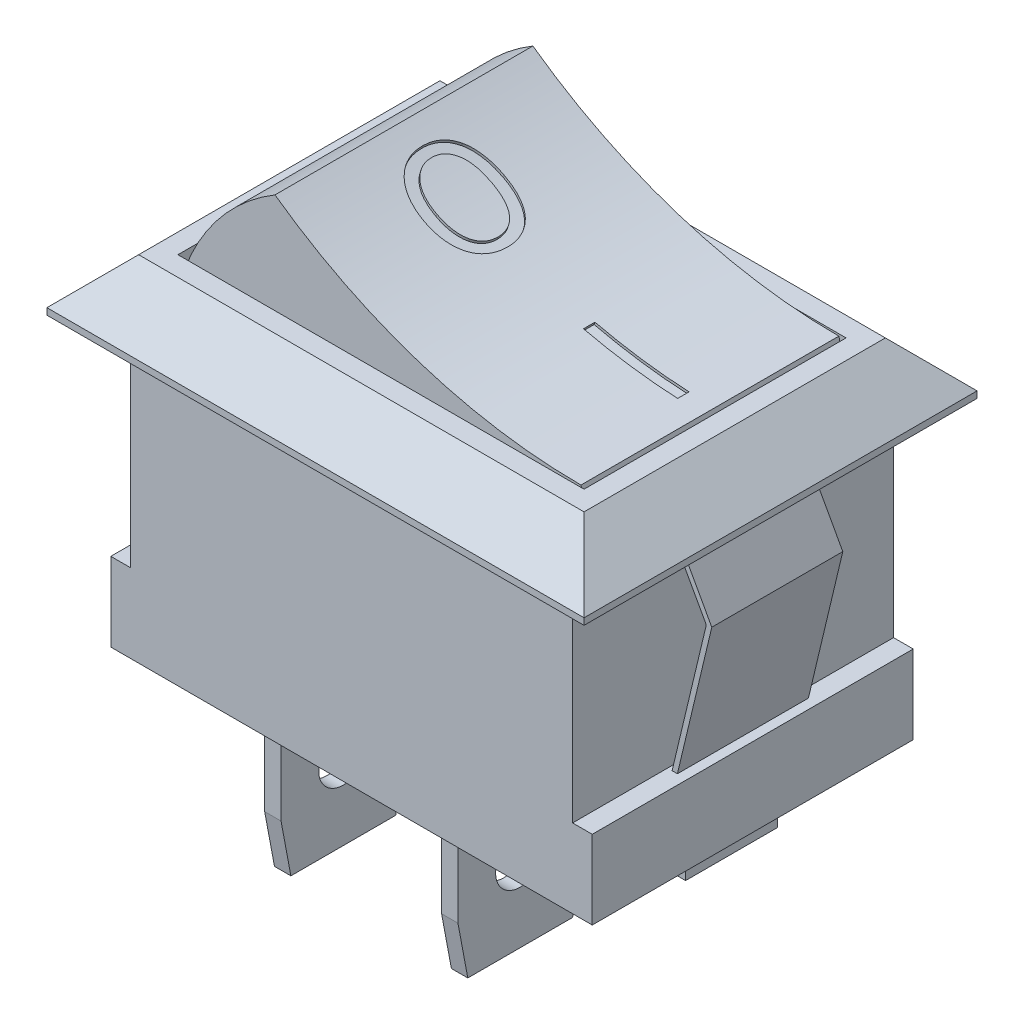
SolidWorks part; units mm, degrees
ref_plane "Front Plane" through (0, 0, 0) normal (0, 0, 1) x (1, 0, 0)
ref_plane "Top Plane" through (0, 0, 0) normal (0, 1, 0) x (1, 0, 0)
ref_plane "Right Plane" through (0, 0, 0) normal (1, 0, 0) x (0, 0, -1)
sketch "Sketch1" plane through (0, 0, 0) normal (0, 1, 0) x (1, 0, 0)
  line L1 (-9.3345, 6.223) -> (9.3345, 6.223)
  line L2 (-9.3345, 6.223) -> (-9.3345, -6.223)
  line L3 (-9.3345, -6.223) -> (9.3345, -6.223)
  line L4 (9.3345, 6.223) -> (9.3345, -6.223)
  line L5 (-9.3345, 6.223) -> (9.3345, -6.223) construction
  line L6 (-9.3345, -6.223) -> (9.3345, 6.223) construction
  point P0 (0, 0)
  dimension "D1" = 12.446
  dimension "D2" = 18.669
extrude "Boss-Extrude1" add sketch "Sketch1" along normal blind 11.303
sketch "Sketch2" plane through (9.3345, 0, 0) normal (1, 0, 0) x (0, 0, -1)
  line L0 (-6.223, 0) -> (6.223, 0) construction
  line L1 (-6.223, 11.303) -> (6.223, 11.303)
  line L2 (-6.223, 11.303) -> (-6.223, 3.048)
  line L3 (-6.223, 3.048) -> (6.223, 3.048)
  line L4 (6.223, 11.303) -> (6.223, 3.048)
  dimension "D1" = 3.048
extrude "Cut-Extrude1" cut sketch "Sketch2" against normal blind 0.762
sketch "Sketch3" plane through (0, 0, 0) normal (0, 0, 1) x (1, 0, 0)
  line L0 (8.2261, 0) -> (10.287, 8.636)
  line L1 (10.287, 8.636) -> (8.8725, 11.203)
  line L2 (0, 0) -> (0, 11.303) construction
  line L3 (-9.3345, 0) -> (9.3345, 0) construction
  line L4 (-9.3345, 11.303) -> (8.5725, 11.303) construction
  line L5 (0, 8.636) -> (10.287, 8.636) construction
  line L6 (8.5725, 3.048) -> (9.3345, 3.048) construction
  line L7 (8.5725, 11.303) -> (8.5725, 3.048) construction
  point P15 (8.9535, 3.048)
  dimension "D1" = 10.287
  dimension "D2" = 8.636
  dimension "D3" = 0.3
  dimension "D4" = 0.1
extrude "Extrude-Thin1" add sketch "Sketch3" along normal mid plane 5.08 thin thin type one direction reverse wall 0.2
mirror "Mirror1" about plane through (0, 0, 0) normal (1, 0, 0) of "Cut-Extrude1", "Extrude-Thin1"
sketch "Sketch4" plane through (0, 11.303, 0) normal (0, 1, 0) x (1, 0, 0)
  line L1 (-10.414, 7.62) -> (10.414, 7.62)
  line L2 (-10.414, 7.62) -> (-10.414, -7.62)
  line L3 (-10.414, -7.62) -> (10.414, -7.62)
  line L4 (10.414, 7.62) -> (10.414, -7.62)
  line L5 (-10.414, 7.62) -> (10.414, -7.62) construction
  line L6 (-10.414, -7.62) -> (10.414, 7.62) construction
  point P0 (0, 0)
  dimension "D1" = 20.828
  dimension "D2" = 15.24
extrude "Boss-Extrude4" add sketch "Sketch4" along normal blind 2.032 contours L4 L3 L2 L1
chamfer "Chamfer1" distance 1.778 angle 45 4 edges at (10.414, 13.335, 0) (0, 13.335, 7.62) (-10.414, 13.335, 0) (0, 13.335, -7.62)
sketch "Sketch5" plane through (0, 13.335, 0) normal (0, 1, 0) x (1, 0, 0)
  line L8 (-7.874, -5.08) -> (7.874, -5.08)
  line L9 (7.874, -5.08) -> (7.874, 5.08)
  line L10 (7.874, 5.08) -> (-7.874, 5.08)
  line L11 (-7.874, 5.08) -> (-7.874, -5.08)
  line L12 (-7.874, -5.08) -> (7.874, -5.08)
  line L13 (7.874, -5.08) -> (7.874, 5.08)
  line L14 (7.874, 5.08) -> (-7.874, 5.08)
  line L15 (-7.874, 5.08) -> (-7.874, -5.08)
  dimension "D1" = 0.762
extrude "Cut-Extrude2" cut sketch "Sketch5" against normal blind 1
sketch "Sketch6" plane through (0, 0, 0) normal (0, 0, 1) x (1, 0, 0)
  line L0 (-8.636, 13.335) -> (8.636, 13.335) construction
  line L5 (0, 10.1209) -> (0, 17.145) construction
  line L6 (0, 17.145) -> (-4.191, 17.145) construction
  line L7 (7.674, 33.7148) -> (7.674, 13.335) construction
  line L8 (7.874, 12.335) -> (7.874, 13.335) construction
  line L9 (-7.874, 12.335) -> (-7.874, 13.335) construction
  line L10 (7.874, 12.335) -> (-7.874, 12.335) construction
  line L11 (7.874, 12.335) -> (-7.874, 12.335)
  arc A0 (-4.191, 17.145) -> (7.674, 13.335) centre (7.674, 33.7148) ccw
  arc A1 (-4.191, 17.145) -> (-7.874, 12.335) centre (0, 10.1209) ccw
  arc A2 (7.874, 12.335) -> (7.674, 13.335) centre (-0.2309, 11.234) ccw
  dimension "D1" = 3.683
  dimension "D2" = 3.81
  dimension "D3" = 0.2
extrude "Boss-Extrude5" add sketch "Sketch6" along normal mid plane 10
ref_plane "Plane1" through (4.5991, 14.3224, 0) normal (-0.3057, -0.9521, 0) x (-0.9521, 0.3057, 0)
sketch "Sketch7" plane through (4.5991, 14.3224, 0) normal (-0.3057, -0.9521, 0) x (-0.9521, 0.3057, 0)
  line L0 (9.2322, 0) -> (-3.2295, 0) construction
  line L1 (-3.2295, -5) -> (-3.2295, 5) construction
  line L2 (9.2322, -5) -> (9.2322, 5) construction
  line L3 (1.3705, -5) -> (1.3705, 5) construction
  line L7 (-3.2295, -5) -> (9.2322, -5) construction
  line L9 (9.2322, 5) -> (-3.2295, 5) construction
  text T0 "l\r\nO\r\n" font "Tahoma" height 3.5
  dimension "D1" = 4.6
extrude "Cut-Extrude4" cut sketch "Sketch7" along normal offset from surface (0.3879 mm away) 0.1 up to face at (1.5923, 14.7754, 0) offset beyond the face yes
sketch "Sketch8" plane through (0, 0, 0) normal (0, -1, 0) x (1, 0, 0)
  line L0 (-6.858, 2.9845) -> (-6.858, -2.9845)
  line L1 (0, 2.9845) -> (0, -2.9845)
  line L2 (6.858, 2.9845) -> (6.858, -2.9845)
  line L3 (-6.858, 0) -> (0, 0) construction
  line L4 (0, 0) -> (6.858, 0) construction
  dimension "D1" = 6.858
  dimension "D2" = 5.969
extrude "Cut-Extrude-Thin1" cut sketch "Sketch8" against normal blind 0.5 thin thin type mid plane wall 0.762
sketch "Sketch9" plane through (0, 0, 0) normal (0, -1, 0) x (1, 0, 0)
  line L0 (-7.239, 2.9845) -> (-7.239, -2.9845) construction
  line L1 (-8.509, 1.778) -> (-7.239, 1.778)
  line L2 (-8.509, 1.778) -> (-8.509, -1.778)
  line L3 (-8.509, -1.778) -> (-7.239, -1.778)
  line L4 (-7.239, 1.778) -> (-7.239, -1.778)
  line L5 (-6.477, 2.9845) -> (-6.477, -2.9845) construction
  line L6 (-6.477, 1.778) -> (-5.207, 1.778)
  line L7 (-6.477, 1.778) -> (-6.477, -1.778)
  line L8 (-6.477, -1.778) -> (-5.207, -1.778)
  line L9 (-5.207, 1.778) -> (-5.207, -1.778)
  line L10 (-0.381, 2.9845) -> (-0.381, -2.9845) construction
  line L11 (-1.651, 1.778) -> (-0.381, 1.778)
  line L12 (-1.651, 1.778) -> (-1.651, -1.778)
  line L13 (-1.651, -1.778) -> (-0.381, -1.778)
  line L14 (-0.381, 1.778) -> (-0.381, -1.778)
  line L15 (0.381, 2.9845) -> (0.381, -2.9845) construction
  line L16 (0.381, 1.778) -> (1.651, 1.778)
  line L17 (0.381, 1.778) -> (0.381, -1.778)
  line L18 (0.381, -1.778) -> (1.651, -1.778)
  line L19 (1.651, 1.778) -> (1.651, -1.778)
  line L20 (6.477, 2.9845) -> (6.477, -2.9845) construction
  line L21 (5.207, 1.778) -> (6.477, 1.778)
  line L22 (5.207, 1.778) -> (5.207, -1.778)
  line L23 (5.207, -1.778) -> (6.477, -1.778)
  line L24 (6.477, 1.778) -> (6.477, -1.778)
  line L25 (7.239, 2.9845) -> (7.239, -2.9845) construction
  line L26 (7.239, 1.778) -> (8.509, 1.778)
  line L27 (7.239, 1.778) -> (7.239, -1.778)
  line L28 (7.239, -1.778) -> (8.509, -1.778)
  line L29 (8.509, 1.778) -> (8.509, -1.778)
  line L30 (-8.509, 0) -> (8.509, 0) construction
  dimension "D1" = 3.556
  dimension "D2" = 1.27
extrude "Boss-Extrude6" add sketch "Sketch9" along normal blind 1.143
sketch "Sketch10" plane through (0, 0, 0) normal (1, 0, 0) x (0, 0, -1)
  line L0 (-2.9845, 0.5) -> (2.9845, 0.5) construction
  line L1 (2.9845, -0.5) -> (2.413, 0)
  line L2 (2.9845, -0.5) -> (2.9845, 0.5)
  line L3 (2.9845, 0.5) -> (-2.9845, 0.5)
  line L4 (-2.9845, -0.5) -> (-2.9845, 0.5)
  line L5 (2.413, -6.35) -> (2.032, -8.382)
  line L6 (2.9845, 0.5) -> (2.9845, 0) construction
  line L7 (-2.9845, 0.5) -> (-2.9845, 0) construction
  line L8 (-2.032, -8.382) -> (-2.413, -6.35)
  line L9 (-2.413, 0) -> (-2.9845, -0.5)
  line L11 (2.413, 0) -> (2.413, -6.35)
  line L12 (2.032, -8.382) -> (-2.032, -8.382)
  line L13 (-2.413, 0) -> (-2.413, -6.35)
  line L14 (0, 0) -> (0, -8.382) construction
  line L15 (-6.223, 0) -> (6.223, 0) construction
  line L16 (1.778, 0) -> (-1.778, 0) construction
  line L17 (2.413, -6.35) -> (-2.413, -6.35) construction
  circle A0 centre (0, -5.3975) radius 0.9525
  dimension "D6" = 1.905
  dimension "D1" = 4.826
  dimension "D2" = 0.5
  dimension "D3" = 8.382
  dimension "D4" = 4.064
  dimension "D5" = 2.032
extrude "Boss-Extrude7" add sketch "Sketch10" along normal mid plane 0.635 separate body
pattern_linear "LPattern1" count 2 spacing 6.86 along (-1, 0, 0) of bodies 111
